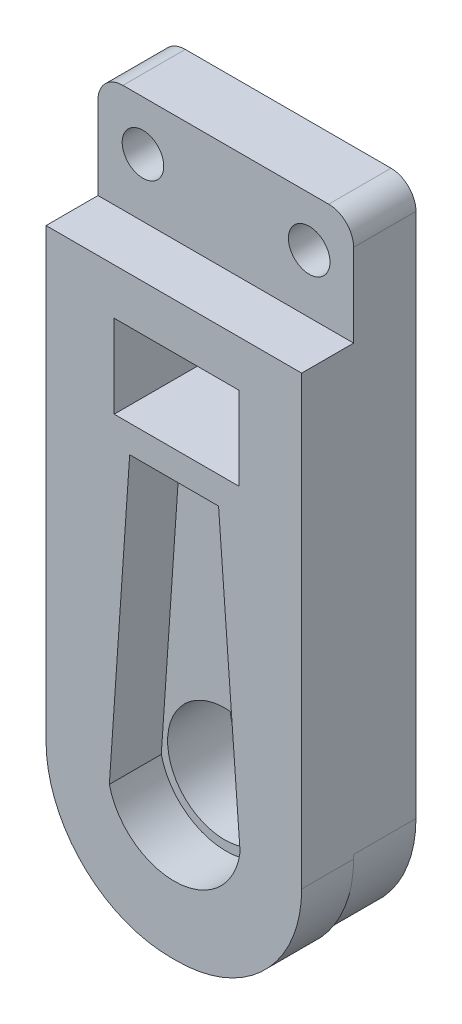
SolidWorks part; units mm, degrees
ref_plane "Front Plane" through (0, 0, 0) normal (0, 0, 1) x (1, 0, 0)
ref_plane "Top Plane" through (0, 0, 0) normal (0, 1, 0) x (1, 0, 0)
ref_plane "Right Plane" through (0, 0, 0) normal (1, 0, 0) x (0, 0, -1)
other "Graphic1"
ref_plane "Plane1" through (0, 0, 10) normal (0, 0, 1) x (1, 0, 0)
sketch "Sketch1" plane through (0, 0, 10) normal (0, 0, 1) x (1, 0, 0)
  line L1 (-188.1625, 126.2158) -> (-175.8625, 126.2158)
  line L2 (-188.1625, 126.2158) -> (-188.1625, 93.7158)
  line L3 (-188.1625, 93.7158) -> (-175.8625, 93.7158)
  line L4 (-175.8625, 126.2158) -> (-175.8625, 93.7158)
  circle A0 centre (-185.9994, 123.8277) radius 1
  circle A1 centre (-177.9994, 123.8277) radius 1
  dimension "D3" = 8
  dimension "D1" = 12.3
  dimension "D2" = 32.5
extrude "Boss-Extrude1" add sketch "Sketch1" along normal blind 3
fillet "Fillet1" radius 1.2 2 edges at (-175.8625, 126.2158, 11.5) (-188.1625, 126.2158, 11.5)
fillet "Fillet2" radius 6 2 edges at (-188.1625, 93.7158, 11.5) (-175.8625, 93.7158, 11.5)
sketch "Sketch2" plane through (0, 0, 13) normal (0, 0, 1) x (1, 0, 0)
  line L0 (-188.1625, 125.0158) -> (-188.1625, 99.7158) construction
  line L1 (-188.1625, 121.0256) -> (-175.8625, 121.0256)
  line L2 (-188.1625, 121.0256) -> (-188.1625, 93.5256)
  line L3 (-188.1625, 93.5256) -> (-175.8625, 93.5256)
  line L4 (-175.8625, 121.0256) -> (-175.8625, 93.5256)
  dimension "D1" = 12.3
  dimension "D2" = 27.5
extrude "Boss-Extrude2" add sketch "Sketch2" along normal blind 2.5
fillet "Fillet3" radius 6 2 edges at (-188.1625, 93.5256, 14.25) (-175.8625, 93.5256, 14.25)
sketch "Sketch3" plane through (0, 0, 15.5) normal (0, 0, 1) x (1, 0, 0)
  line L1 (-184.8835, 118.8029) -> (-178.8835, 118.8029)
  line L2 (-184.8835, 118.8029) -> (-184.8835, 114.8029)
  line L3 (-184.8835, 114.8029) -> (-178.8835, 114.8029)
  line L4 (-178.8835, 118.8029) -> (-178.8835, 114.8029)
  dimension "D1" = 6
  dimension "D2" = 4
extrude "Cut-Extrude1" cut sketch "Sketch3" against normal through all
sketch "Sketch4" plane through (0, 0, 15.5) normal (0, 0, 1) x (1, 0, 0)
  line L0 (-184.1384, 113.486) -> (-179.8616, 113.486)
  line L1 (-179.8616, 113.486) -> (-178.8249, 99.587)
  line L2 (-184.1384, 113.486) -> (-185.1166, 99.2597)
  arc A0 (-185.1166, 99.2597) -> (-178.8249, 99.587) centre (-182, 99.9854) ccw
extrude "Cut-Extrude2" cut sketch "Sketch4" against normal blind 2.5
sketch "Sketch5" plane through (0, 0, 13) normal (0, 0, 1) x (1, 0, 0)
  line L0 (-175.8625, 99.5256) -> (-175.8625, 121.0256) construction
  circle A0 centre (-182.0625, 99.9727) radius 2.75
  dimension "D1" = 5.5
  dimension "D2" = 6.2
extrude "Cut-Extrude3" cut sketch "Sketch5" against normal through all
